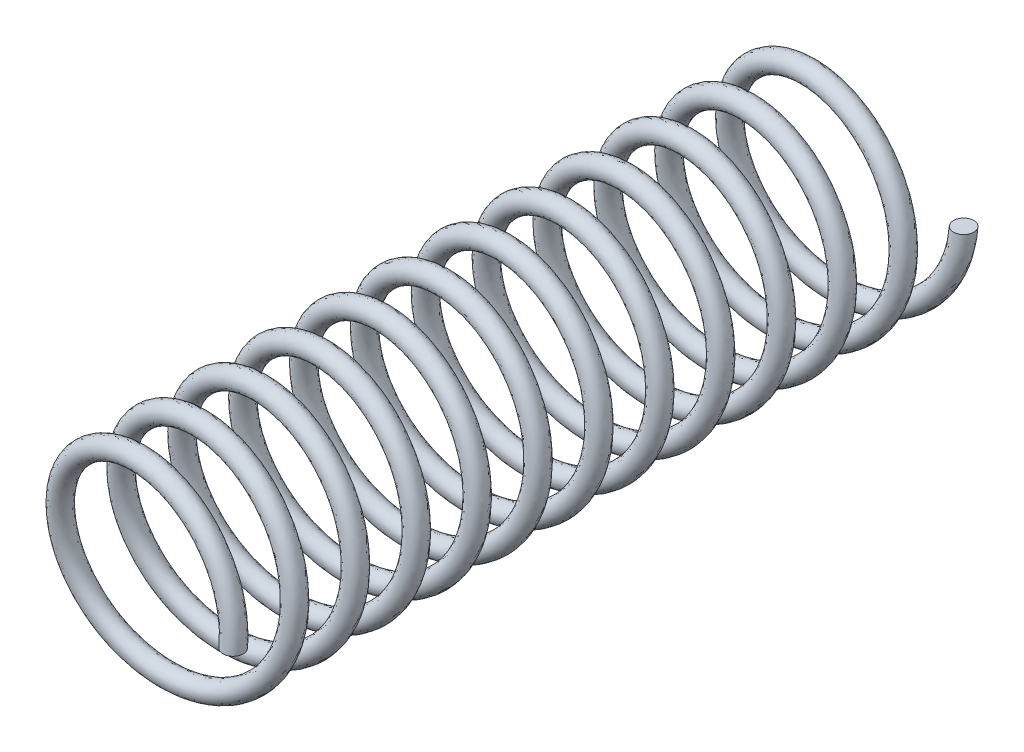
SolidWorks part; units mm, degrees
ref_plane "前基準面" through (0, 0, 0) normal (0, 0, 1) x (1, 0, 0)
ref_plane "上基準面" through (0, 0, 0) normal (0, 1, 0) x (1, 0, 0)
ref_plane "右基準面" through (0, 0, 0) normal (1, 0, 0) x (0, 0, -1)
sketch "草圖1" plane through (0, 0, 0) normal (0, 0, 1) x (1, 0, 0)
  circle A0 centre (0, 0) radius 5
  dimension "D1" = 10
curve "螺旋曲線/渦捲線1" pitch 3 height 36 turns 12
sketch "草圖6" plane through (0, 0, 0) normal (0, 1, 0) x (1, 0, 0)
  circle A0 centre (5, 0) radius 0.5
  spline S0 degree 3 poles (5, 0) (5, -0.0621) (4.7397, -0.1877) (3.6276, -0.375) (1.9632, -0.5625) (0, -0.75) (-1.9632, -0.9375) (-3.6276, -1.125) (-4.7397, -1.3125) (-5.1302, -1.5) (-4.7397, -1.6875) (-3.6276, -1.875) (-1.9632, -2.0625) (0, -2.25) (1.9632, -2.4375) (3.6276, -2.625) (4.7397, -2.8125) (5.1302, -3) (4.7397, -3.1875) (3.6276, -3.375) (1.9632, -3.5625) (0, -3.75) (-1.9632, -3.9375) (-3.6276, -4.125) (-4.7397, -4.3125) (-5.1302, -4.5) (-4.7397, -4.6875) (-3.6276, -4.875) (-1.9632, -5.0625) (0, -5.25) (1.9632, -5.4375) (3.6276, -5.625) (4.7397, -5.8125) (5.1302, -6) (4.7397, -6.1875) (3.6276, -6.375) (1.9632, -6.5625) (0, -6.75) (-1.9632, -6.9375) (-3.6276, -7.125) (-4.7397, -7.3125) (-5.1302, -7.5) (-4.7397, -7.6875) (-3.6276, -7.875) (-1.9632, -8.0625) (0, -8.25) (1.9632, -8.4375) (3.6276, -8.625) (4.7397, -8.8125) (5.1302, -9) (4.7397, -9.1875) (3.6276, -9.375) (1.9632, -9.5625) (0, -9.75) (-1.9632, -9.9375) (-3.6276, -10.125) (-4.7397, -10.3125) (-5.1302, -10.5) (-4.7397, -10.6875) (-3.6276, -10.875) (-1.9632, -11.0625) (0, -11.25) (1.9632, -11.4375) (3.6276, -11.625) (4.7397, -11.8125) (5.1302, -12) (4.7397, -12.1875) (3.6276, -12.375) (1.9632, -12.5625) (0, -12.75) (-1.9632, -12.9375) (-3.6276, -13.125) (-4.7397, -13.3125) (-5.1302, -13.5) (-4.7397, -13.6875) (-3.6276, -13.875) (-1.9632, -14.0625) (0, -14.25) (1.9632, -14.4375) (3.6276, -14.625) (4.7397, -14.8125) (5.1302, -15) (4.7397, -15.1875) (3.6276, -15.375) (1.9632, -15.5625) (0, -15.75) (-1.9632, -15.9375) (-3.6276, -16.125) (-4.7397, -16.3125) (-5.1302, -16.5) (-4.7397, -16.6875) (-3.6276, -16.875) (-1.9632, -17.0625) (0, -17.25) (1.9632, -17.4375) (3.6276, -17.625) (4.7397, -17.8125) (5.1302, -18) (4.7397, -18.1875) (3.6276, -18.375) (1.9632, -18.5625) (0, -18.75) (-1.9632, -18.9375) (-3.6276, -19.125) (-4.7397, -19.3125) (-5.1302, -19.5) (-4.7397, -19.6875) (-3.6276, -19.875) (-1.9632, -20.0625) (0, -20.25) (1.9632, -20.4375) (3.6276, -20.625) (4.7397, -20.8125) (5.1302, -21) (4.7397, -21.1875) (3.6276, -21.375) (1.9632, -21.5625) (0, -21.75) (-1.9632, -21.9375) (-3.6276, -22.125) (-4.7397, -22.3125) (-5.1302, -22.5) (-4.7397, -22.6875) (-3.6276, -22.875) (-1.9632, -23.0625) (0, -23.25) (1.9632, -23.4375) (3.6276, -23.625) (4.7397, -23.8125) (5.1302, -24) (4.7397, -24.1875) (3.6276, -24.375) (1.9632, -24.5625) (0, -24.75) (-1.9632, -24.9375) (-3.6276, -25.125) (-4.7397, -25.3125) (-5.1302, -25.5) (-4.7397, -25.6875) (-3.6276, -25.875) (-1.9632, -26.0625) (0, -26.25) (1.9632, -26.4375) (3.6276, -26.625) (4.7397, -26.8125) (5.1302, -27) (4.7397, -27.1875) (3.6276, -27.375) (1.9632, -27.5625) (0, -27.75) (-1.9632, -27.9375) (-3.6276, -28.125) (-4.7397, -28.3125) (-5.1302, -28.5) (-4.7397, -28.6875) (-3.6276, -28.875) (-1.9632, -29.0625) (0, -29.25) (1.9632, -29.4375) (3.6276, -29.625) (4.7397, -29.8125) (5.1302, -30) (4.7397, -30.1875) (3.6276, -30.375) (1.9632, -30.5625) (0, -30.75) (-1.9632, -30.9375) (-3.6276, -31.125) (-4.7397, -31.3125) (-5.1302, -31.5) (-4.7397, -31.6875) (-3.6276, -31.875) (-1.9632, -32.0625) (0, -32.25) (1.9632, -32.4375) (3.6276, -32.625) (4.7397, -32.8125) (5.1302, -33) (4.7397, -33.1875) (3.6276, -33.375) (1.9632, -33.5625) (0, -33.75) (-1.9632, -33.9375) (-3.6276, -34.125) (-4.7397, -34.3125) (-5.1302, -34.5) (-4.7397, -34.6875) (-3.6276, -34.875) (-1.9632, -35.0625) (0, -35.25) (1.9632, -35.4375) (3.6276, -35.625) (4.7397, -35.8123) (5, -35.9379) (5, -36) knots 0 0 0 0 0.005208 0.010417 0.015625 0.020833 0.026042 0.03125 0.036458 0.041667 0.046875 0.052083 0.057292 0.0625 0.067708 0.072917 0.078125 0.083333 0.088542 0.09375 0.098958 0.104167 0.109375 0.114583 0.119792 0.125 0.130208 0.135417 0.140625 0.145833 0.151042 0.15625 0.161458 0.166667 0.171875 0.177083 0.182292 0.1875 0.192708 0.197917 0.203125 0.208333 0.213542 0.21875 0.223958 0.229167 0.234375 0.239583 0.244792 0.25 0.255208 0.260417 0.265625 0.270833 0.276042 0.28125 0.286458 0.291667 0.296875 0.302083 0.307292 0.3125 0.317708 0.322917 0.328125 0.333333 0.338542 0.34375 0.348958 0.354167 0.359375 0.364583 0.369792 0.375 0.380208 0.385417 0.390625 0.395833 0.401042 0.40625 0.411458 0.416667 0.421875 0.427083 0.432292 0.4375 0.442708 0.447917 0.453125 0.458333 0.463542 0.46875 0.473958 0.479167 0.484375 0.489583 0.494792 0.5 0.505208 0.510417 0.515625 0.520833 0.526042 0.53125 0.536458 0.541667 0.546875 0.552083 0.557292 0.5625 0.567708 0.572917 0.578125 0.583333 0.588542 0.59375 0.598958 0.604167 0.609375 0.614583 0.619792 0.625 0.630208 0.635417 0.640625 0.645833 0.651042 0.65625 0.661458 0.666667 0.671875 0.677083 0.682292 0.6875 0.692708 0.697917 0.703125 0.708333 0.713542 0.71875 0.723958 0.729167 0.734375 0.739583 0.744792 0.75 0.755208 0.760417 0.765625 0.770833 0.776042 0.78125 0.786458 0.791667 0.796875 0.802083 0.807292 0.8125 0.817708 0.822917 0.828125 0.833333 0.838542 0.84375 0.848958 0.854167 0.859375 0.864583 0.869792 0.875 0.880208 0.885417 0.890625 0.895833 0.901042 0.90625 0.911458 0.916667 0.921875 0.927083 0.932292 0.9375 0.942708 0.947917 0.953125 0.958333 0.963542 0.96875 0.973958 0.979167 0.984375 0.989583 0.994792 1 1 1 1 construction
  dimension "D1" = 1
sweep "掃出1" add profiles "草圖6" path "螺旋曲線/渦捲線1"
